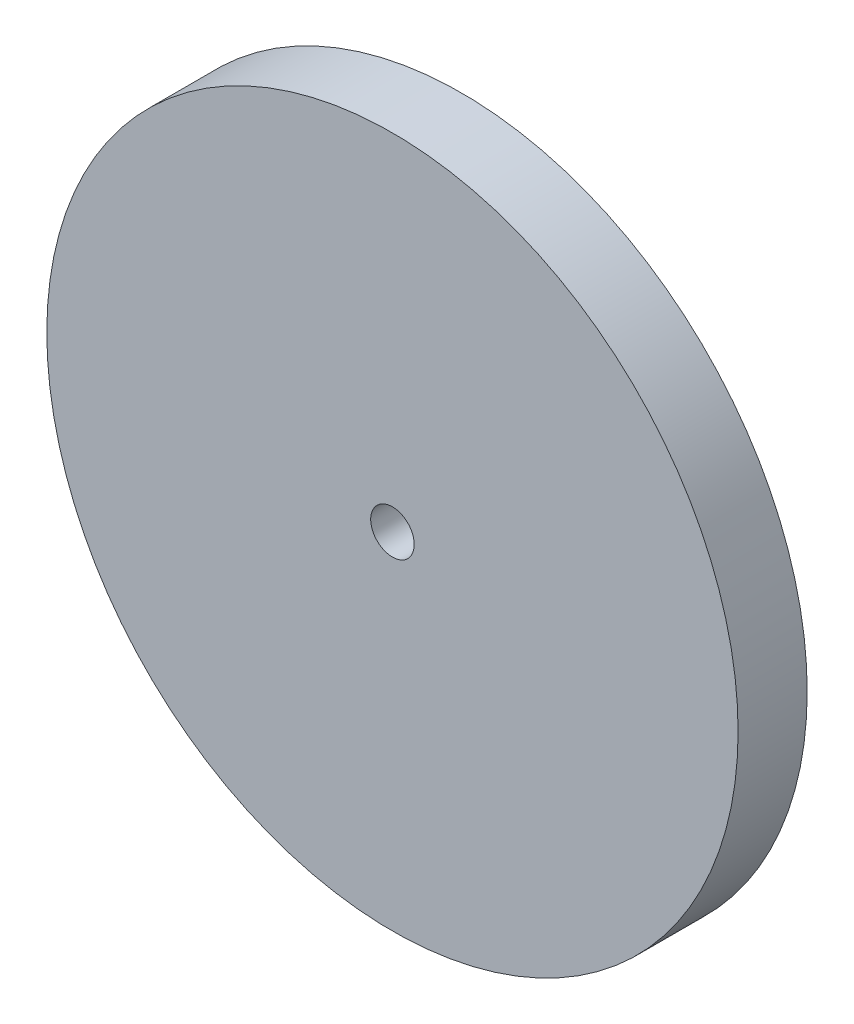
SolidWorks part; units mm, degrees
material "Acrylic (Medium-high impact)"
ref_plane "Front Plane" through (0, 0, 0) normal (0, 0, 1) x (1, 0, 0)
ref_plane "Top Plane" through (0, 0, 0) normal (0, 1, 0) x (1, 0, 0)
ref_plane "Right Plane" through (0, 0, 0) normal (1, 0, 0) x (0, 0, -1)
sketch "Sketch1" plane through (0, 0, 0) normal (0, 0, 1) x (1, 0, 0)
  circle A1 centre (0, 0) radius 23.8252
  circle A2 centre (0, 0) radius 23.8252
  dimension "D1" = 0
extrude "Boss-Extrude1" add sketch "Sketch1" along normal blind 4.7625
sketch "Sketch2" plane through (0, 0, 4.7625) normal (0, 0, 1) x (1, 0, 0)
  circle A0 centre (0, 0) radius 1.5
  dimension "D1" = 3
extrude "Cut-Extrude1" cut sketch "Sketch2" against normal through all
